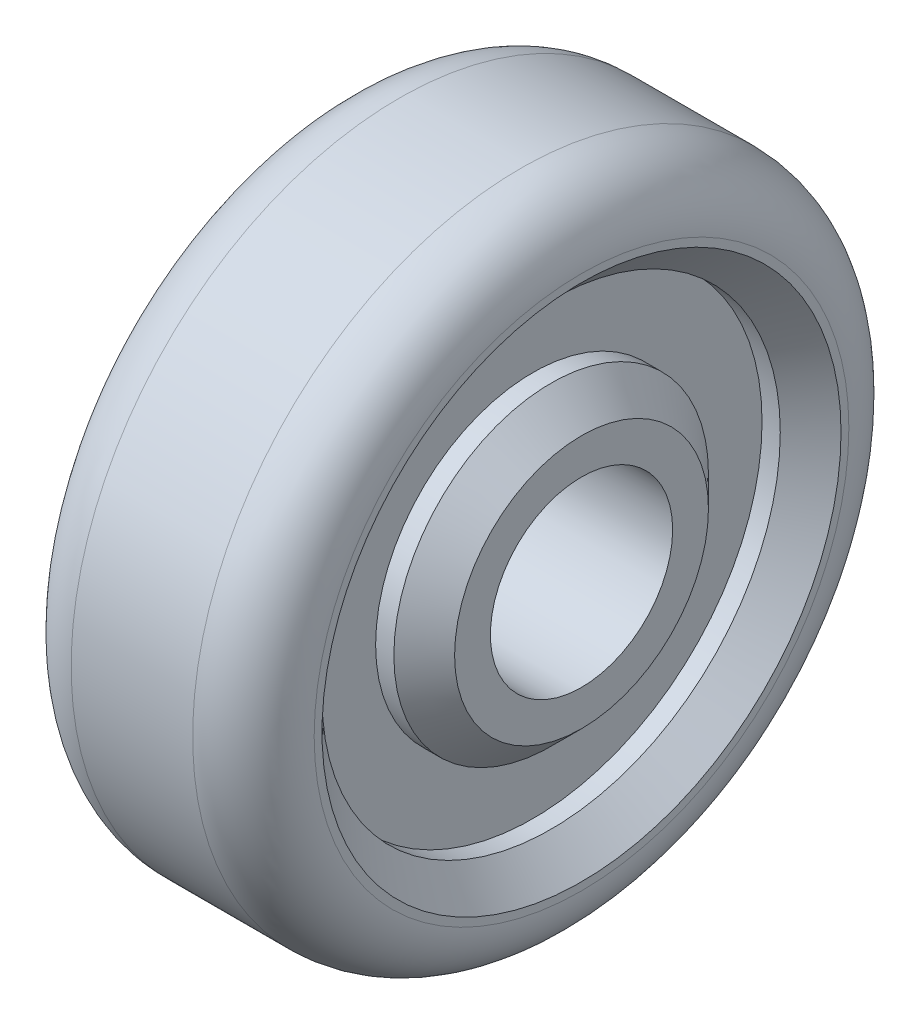
SolidWorks part; units mm, degrees
ref_plane "前视基准面" through (0, 0, 0) normal (0, 0, 1) x (1, 0, 0)
ref_plane "上视基准面" through (0, 0, 0) normal (0, 1, 0) x (1, 0, 0)
ref_plane "右视基准面" through (0, 0, 0) normal (1, 0, 0) x (0, 0, -1)
sketch "草图1" plane through (0, 0, 0) normal (1, 0, 0) x (0, 0, -1)
  circle A0 centre (0, 0) radius 54
  circle A1 centre (0, 0) radius 15
  dimension "D1" = 108
  dimension "D2" = 30
extrude "凸台-拉伸1" add sketch "草图1" along normal mid plane 40
fillet "圆角1" radius 10 2 edges at (-20, 0, -54) (20, 0, -54)
sketch "草图2" plane through (20, 0, 0) normal (1, 0, 0) x (0, 0, -1)
  circle A0 centre (0, 0) radius 25.8892
  circle A1 centre (0, 0) radius 37.7115
extrude "切除-拉伸1" cut sketch "草图2" against normal blind 8
chamfer "倒角1" distance 5 angle 45 2 edges at (20, 0, -25.8892) (20, 0, -37.7115)
mirror "镜向4" about plane through (0, 0, 0) normal (1, 0, 0) of "切除-拉伸1", "倒角1"
